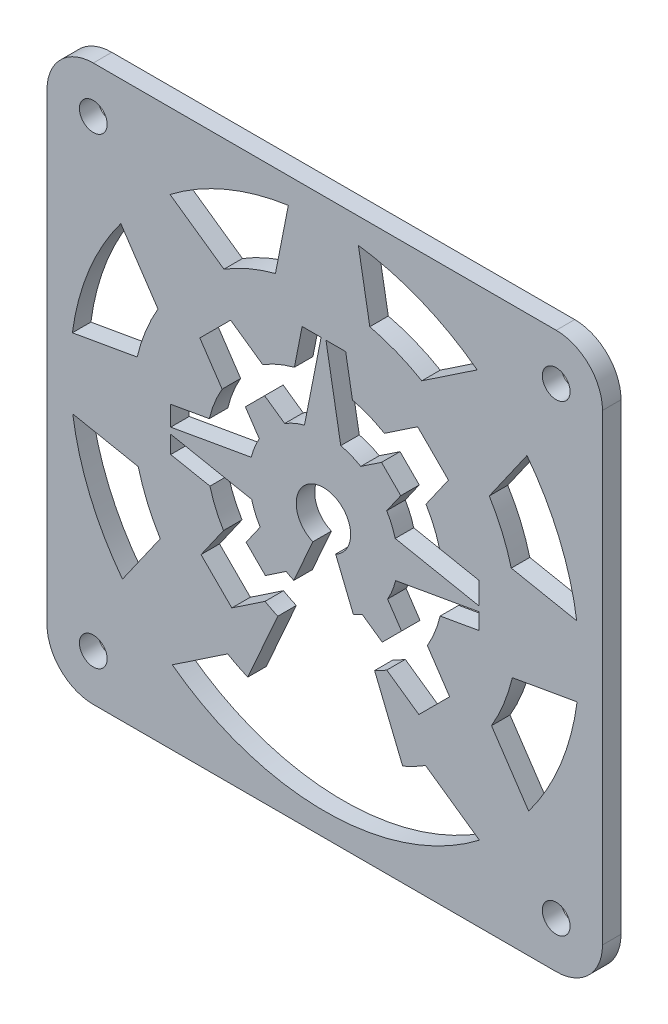
SolidWorks part; units mm, degrees
ref_plane "Piano frontale" through (0, 0, 0) normal (0, 0, 1) x (1, 0, 0)
ref_plane "Piano superiore" through (0, 0, 0) normal (0, 1, 0) x (1, 0, 0)
ref_plane "Piano destro" through (0, 0, 0) normal (1, 0, 0) x (0, 0, -1)
sketch "Schizzo1" plane through (0, 0, 0) normal (0, 0, 1) x (1, 0, 0)
  line L0 (4.0091, 37.0789) -> (4.0091, -12.9211)
  line L1 (-25.9909, 42.0789) -> (-25.9909, -17.9211) construction
  line L2 (-55.9909, 12.0789) -> (4.0091, 12.0789) construction
  line L3 (-31.3157, 32.2263) -> (-29.9228, 39.2964)
  line L5 (-0.9909, -17.9211) -> (-50.9909, -17.9211)
  line L6 (-55.9909, 37.0789) -> (-55.9909, -12.9211)
  line L7 (-0.9909, 42.0789) -> (-50.9909, 42.0789)
  line L8 (-22.3584, 39.338) -> (-21.125, 32.342)
  line L9 (-15.5098, 30.0905) -> (-9.5255, 34.1049)
  line L11 (-4.1473, 28.7854) -> (-8.222, 22.9664)
  line L12 (-5.8436, 17.4037) -> (1.2265, 16.0108)
  line L14 (1.2681, 8.4465) -> (-5.7278, 7.213)
  line L15 (-7.9794, 1.5978) -> (-3.965, -4.3864)
  line L17 (-9.2845, -9.7647) -> (-15.1035, -5.6899)
  line L18 (-36.4721, -5.9326) -> (-42.4563, -9.947)
  line L20 (-47.8346, -4.6275) -> (-43.7598, 1.1915)
  line L21 (-46.1383, 6.7542) -> (-53.2084, 8.1471)
  line L23 (-53.25, 15.7114) -> (-46.254, 16.9449)
  line L24 (-44.0025, 22.5601) -> (-48.0169, 28.5443)
  line L26 (-42.6974, 33.9226) -> (-36.8784, 29.8478)
  line L27 (-34.3059, -7.0295) -> (-28.9664, 5.0325)
  line L28 (-22.5663, 5.2396) -> (-17.5751, -6.9852)
  arc A0 (4.0091, 37.0789) -> (-0.9909, 42.0789) centre (-0.9909, 37.0789) ccw
  arc A1 (-50.9909, 42.0789) -> (-55.9909, 37.0789) centre (-50.9909, 37.0789) ccw
  arc A2 (-55.9909, -12.9211) -> (-50.9909, -17.9211) centre (-50.9909, -12.9211) ccw
  arc A3 (-0.9909, -17.9211) -> (4.0091, -12.9211) centre (-0.9909, -12.9211) ccw
  circle A4 centre (-50.9909, 37.0789) radius 1.5
  circle A5 centre (-0.9909, 37.0789) radius 1.5
  circle A6 centre (-50.9909, -12.9211) radius 1.5
  circle A7 centre (-0.9909, -12.9211) radius 1.5
  arc A8 (-42.4563, -9.947) -> (-9.2845, -9.7647) centre (-25.9909, 12.0789) ccw
  arc A9 (-22.5663, 5.2396) -> (-28.9664, 5.0325) centre (-25.9909, 12.0789) ccw
  arc A10 (-17.5751, -6.9852) -> (-15.1035, -5.6899) centre (-25.9909, 12.0789) ccw
  arc A11 (-15.5098, 30.0905) -> (-21.125, 32.342) centre (-25.9909, 12.0789) ccw
  arc A12 (-5.8436, 17.4037) -> (-8.222, 22.9664) centre (-25.9909, 12.0789) ccw
  arc A13 (-7.9794, 1.5978) -> (-5.7278, 7.213) centre (-25.9909, 12.0789) ccw
  arc A14 (-31.3157, 32.2263) -> (-36.8784, 29.8478) centre (-25.9909, 12.0789) ccw
  arc A15 (-44.0025, 22.5601) -> (-46.254, 16.9449) centre (-25.9909, 12.0789) ccw
  arc A16 (-46.1383, 6.7542) -> (-43.7598, 1.1915) centre (-25.9909, 12.0789) ccw
  arc A17 (-36.4721, -5.9326) -> (-34.3059, -7.0295) centre (-25.9909, 12.0789) ccw
  arc A18 (-53.2084, 8.1471) -> (-47.8346, -4.6275) centre (-25.9909, 12.0789) ccw
  arc A19 (-48.0169, 28.5443) -> (-53.25, 15.7114) centre (-25.9909, 12.0789) ccw
  arc A20 (-29.9228, 39.2964) -> (-42.6974, 33.9226) centre (-25.9909, 12.0789) ccw
  arc A21 (-9.5255, 34.1049) -> (-22.3584, 39.338) centre (-25.9909, 12.0789) ccw
  arc A22 (1.2265, 16.0108) -> (-4.1473, 28.7854) centre (-25.9909, 12.0789) ccw
  arc A23 (-3.965, -4.3864) -> (1.2681, 8.4465) centre (-25.9909, 12.0789) ccw
  point P58 (-25.9909, 12.0789)
  dimension "D1" = 5
  dimension "D2" = 5
  dimension "D3" = 3
  dimension "D4" = 3
  dimension "D5" = 3
  dimension "D6" = 3
  dimension "D7" = 55
extrude "Estrusione-Estrusione1" add sketch "Schizzo1" along normal blind 2
sketch "Schizzo2" plane through (0, 0, 0) normal (0, 0, 1) x (1, 0, 0)
  line L0 (-29.2677, 24.4773) -> (-28.4329, 28.7148)
  line L1 (-28.4329, 28.7148) -> (-23.7311, 28.7148)
  line L2 (-23.7311, 28.7148) -> (-22.9965, 24.5485)
  line L3 (-19.541, 23.163) -> (-15.9544, 25.569)
  line L4 (-15.9544, 25.569) -> (-12.6297, 22.2443)
  line L5 (-12.6297, 22.2443) -> (-15.0562, 18.7789)
  line L6 (-13.5926, 15.3557) -> (-9.3551, 14.5209)
  line L7 (-9.3551, 14.5209) -> (-9.3551, 9.8191)
  line L8 (-9.3551, 9.8191) -> (-13.5213, 9.0845)
  line L9 (-14.9069, 5.629) -> (-12.5009, 2.0424)
  line L10 (-12.5009, 2.0424) -> (-15.8256, -1.2823)
  line L11 (-15.8256, -1.2823) -> (-19.291, 1.1442)
  line L12 (-32.4409, 0.9949) -> (-36.0275, -1.4111)
  line L13 (-36.0275, -1.4111) -> (-39.3522, 1.9136)
  line L14 (-39.3522, 1.9136) -> (-36.9256, 5.379)
  line L15 (-38.3893, 8.8022) -> (-42.6268, 9.637)
  line L16 (-42.6268, 9.637) -> (-42.6268, 14.3388)
  line L17 (-42.6268, 14.3388) -> (-38.4605, 15.0734)
  line L18 (-37.075, 18.5289) -> (-39.481, 22.1155)
  line L19 (-39.481, 22.1155) -> (-36.1563, 25.4402)
  line L20 (-36.1563, 25.4402) -> (-32.6909, 23.0137)
  line L21 (-30.4021, 0.0374) -> (-27.0969, 7.5037)
  line L22 (-23.8835, 7.8701) -> (-20.8119, 0.3471)
  arc A0 (-23.8835, 7.8701) -> (-27.0969, 7.5037) centre (-25.9909, 12.0789) ccw
  arc A1 (-20.8119, 0.3471) -> (-19.291, 1.1442) centre (-25.9909, 12.0789) ccw
  arc A2 (-19.541, 23.163) -> (-22.9965, 24.5485) centre (-25.9909, 12.0789) ccw
  arc A3 (-13.5926, 15.3557) -> (-15.0562, 18.7789) centre (-25.9909, 12.0789) ccw
  arc A4 (-14.9069, 5.629) -> (-13.5213, 9.0845) centre (-25.9909, 12.0789) ccw
  arc A5 (-29.2677, 24.4773) -> (-32.6909, 23.0137) centre (-25.9909, 12.0789) ccw
  arc A6 (-37.075, 18.5289) -> (-38.4605, 15.0734) centre (-25.9909, 12.0789) ccw
  arc A7 (-38.3893, 8.8022) -> (-36.9256, 5.379) centre (-25.9909, 12.0789) ccw
  arc A8 (-32.4409, 0.9949) -> (-30.4021, 0.0374) centre (-25.9909, 12.0789) ccw
  point P32 (-25.9909, 12.0789)
extrude "Taglio-Estrusione1" cut sketch "Schizzo2" along normal blind 2
sketch "Schizzo3" plane through (0, 0, 0) normal (0, 0, 1) x (1, 0, 0)
  line L0 (-28.1798, 19.6094) -> (-26.3859, 28.7148)
  line L2 (-25.8578, 28.7148) -> (-24.2603, 19.6539)
  line L3 (-22.1006, 18.7879) -> (-19.859, 20.2917)
  line L4 (-19.859, 20.2917) -> (-17.781, 18.2138)
  line L5 (-17.781, 18.2138) -> (-19.2976, 16.0479)
  line L6 (-18.3828, 13.9084) -> (-9.3551, 12.1298)
  line L7 (-26.3859, 28.7148) -> (-25.8578, 28.7148)
  line L8 (-9.3551, 11.5727) -> (-18.3383, 9.9889)
  line L9 (-19.2043, 7.8292) -> (-17.7006, 5.5876)
  line L10 (-17.7006, 5.5876) -> (-19.7785, 3.5096)
  line L11 (-19.7785, 3.5096) -> (-21.9443, 5.0262)
  line L12 (-30.163, 4.9329) -> (-32.4047, 3.4292)
  line L13 (-32.4047, 3.4292) -> (-34.4826, 5.5071)
  line L14 (-34.4826, 5.5071) -> (-32.966, 7.673)
  line L15 (-33.8808, 9.8124) -> (-42.6268, 11.5355)
  line L17 (-42.6268, 12.1978) -> (-33.9253, 13.7319)
  line L18 (-33.0593, 15.8916) -> (-34.5631, 18.1333)
  line L19 (-34.5631, 18.1333) -> (-32.4851, 20.2112)
  line L20 (-32.4851, 20.2112) -> (-30.3193, 18.6946)
  line L21 (-29.3299, 4.511) -> (-27.2762, 9.1503)
  line L22 (-24.8146, 9.2299) -> (-22.8949, 4.5281)
  line L23 (-42.6268, 12.1978) -> (-42.6268, 11.5355)
  line L24 (-9.3551, 12.1298) -> (-9.3551, 11.5727)
  arc A0 (-24.8146, 9.2299) -> (-27.2762, 9.1503) centre (-26.1318, 11.8604) ccw
  arc A1 (-22.8949, 4.5281) -> (-21.9443, 5.0262) centre (-26.1318, 11.8604) ccw
  arc A2 (-22.1006, 18.7879) -> (-24.2603, 19.6539) centre (-26.1318, 11.8604) ccw
  arc A3 (-18.3828, 13.9084) -> (-19.2976, 16.0479) centre (-26.1318, 11.8604) ccw
  arc A4 (-19.2043, 7.8292) -> (-18.3383, 9.9889) centre (-26.1318, 11.8604) ccw
  arc A5 (-28.1798, 19.6094) -> (-30.3193, 18.6946) centre (-26.1318, 11.8604) ccw
  arc A6 (-33.0593, 15.8916) -> (-33.9253, 13.7319) centre (-26.1318, 11.8604) ccw
  arc A7 (-33.8808, 9.8124) -> (-32.966, 7.673) centre (-26.1318, 11.8604) ccw
  arc A8 (-30.163, 4.9329) -> (-29.3299, 4.511) centre (-26.1318, 11.8604) ccw
  point P32 (-26.1318, 11.8604)
extrude "Estrusione-Estrusione2" add sketch "Schizzo3" along normal blind 2
